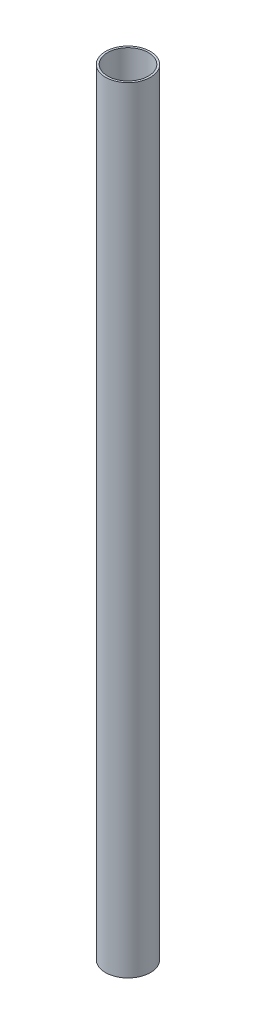
SolidWorks part; units mm, degrees
ref_plane "Front Plane" through (0, 0, 0) normal (0, 0, 1) x (1, 0, 0)
ref_plane "Top Plane" through (0, 0, 0) normal (0, 1, 0) x (1, 0, 0)
ref_plane "Right Plane" through (0, 0, 0) normal (1, 0, 0) x (0, 0, -1)
sketch "Sketch1" plane through (0, 0, 0) normal (0, 1, 0) x (1, 0, 0)
  circle A0 centre (0, 0) radius 27.94
  circle A1 centre (0, 0) radius 25.4
sketch3d "3DSketch1"
  line L0 (0, 0, 0) -> (0, -965.2, 0)
sweep "Sweep2" add profiles "Sketch1" path "3DSketch1"
